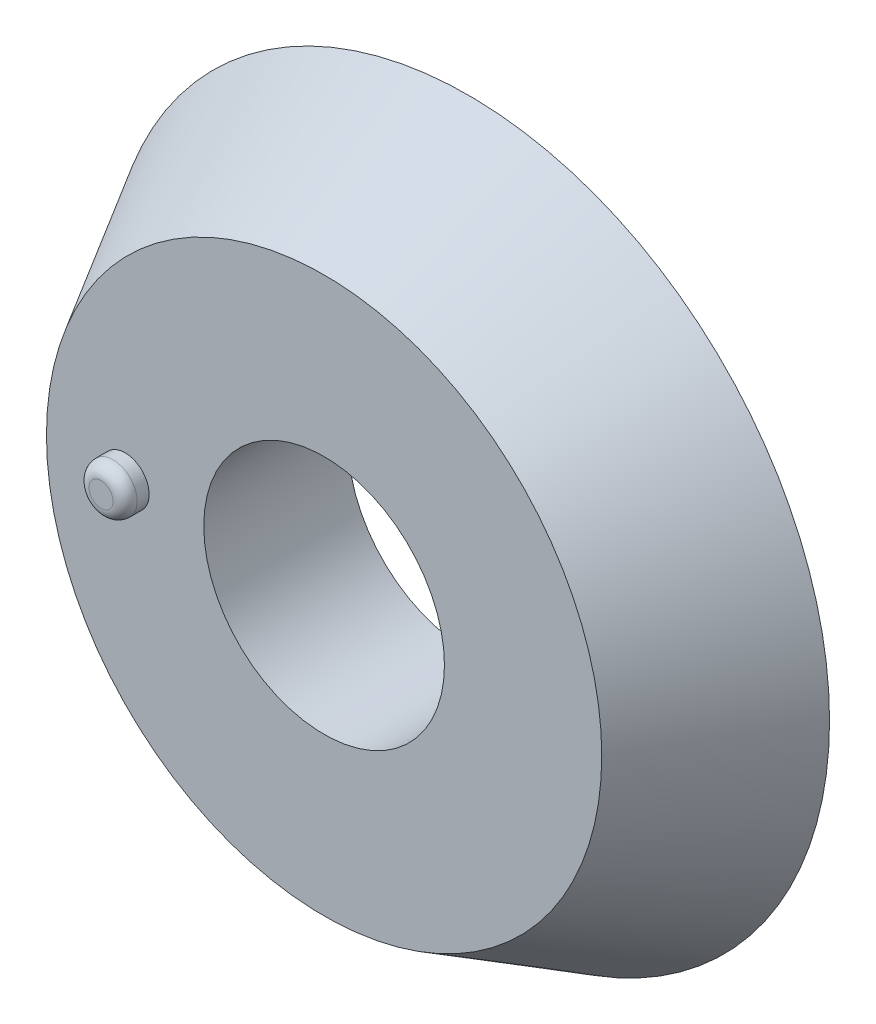
SolidWorks part; units mm, degrees
ref_plane "정면" through (0, 0, 0) normal (0, 0, 1) x (1, 0, 0)
ref_plane "윗면" through (0, 0, 0) normal (0, 1, 0) x (1, 0, 0)
ref_plane "우측면" through (0, 0, 0) normal (1, 0, 0) x (0, 0, -1)
sketch "스케치1" plane through (0, 0, 0) normal (0, 0, 1) x (1, 0, 0)
  circle A0 centre (0, 0) radius 75
  dimension "D1" = 150
extrude "보스-돌출1" add sketch "스케치1" along normal blind 30 draft 30
sketch "스케치2" plane through (0, 0, 30) normal (0, 0, 1) x (1, 0, 0)
  circle A0 centre (0, 0) radius 25
  dimension "D1" = 50
extrude "컷-돌출1" cut sketch "스케치2" against normal through all both and the other way through all
sketch "스케치3" plane through (0, 0, 30) normal (0, 0, 1) x (1, 0, 0)
  line L0 (57.6795, 0) -> (-57.6795, 0)
  line L1 (-57.6795, 0) -> (-25, 0)
  circle A0 centre (0, 0) radius 57.6795 construction
  circle A1 centre (0, 0) radius 25 construction
  circle A2 centre (-41.3397, 0) radius 5
  dimension "D1" = 10
extrude "보스-돌출2" add sketch "스케치3" along normal blind 5 contours L1 A2 | L1 A2
fillet "필렛1" radius 2.5 1 edges at (-36.3397, 0, 35)
